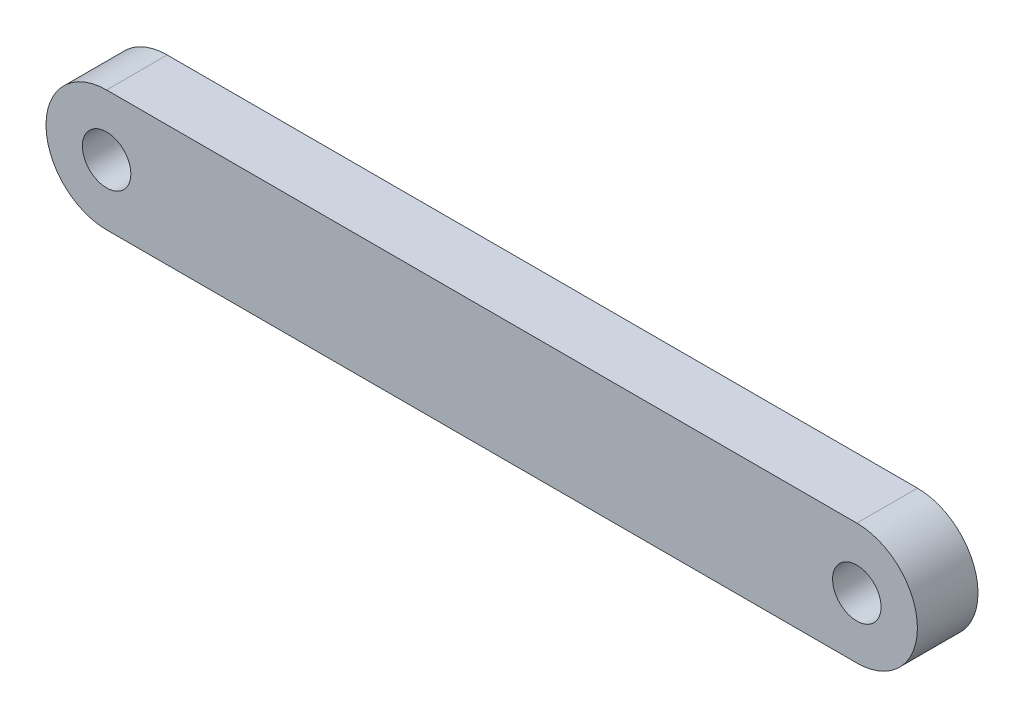
SolidWorks part; units mm, degrees
ref_plane "前基準面" through (0, 0, 0) normal (0, 0, 1) x (1, 0, 0)
ref_plane "上基準面" through (0, 0, 0) normal (0, 1, 0) x (1, 0, 0)
ref_plane "右基準面" through (0, 0, 0) normal (1, 0, 0) x (0, 0, -1)
sketch "草圖2" plane through (0, 0, 0) normal (0, 0, 1) x (1, 0, 0)
  line L0 (-30.95, 0) -> (30.95, 0) construction
  line L1 (-30.95, 5) -> (30.95, 5)
  line L2 (-30.95, -5) -> (30.95, -5)
  arc A0 (-30.95, 5) -> (-30.95, -5) centre (-30.95, 0) ccw
  arc A1 (30.95, -5) -> (30.95, 5) centre (30.95, 0) ccw
  circle A2 centre (30.95, 0) radius 2
  circle A3 centre (-30.95, 0) radius 2
  point P2 (0, 0)
  dimension "D2" = 4
  dimension "D3" = 5
  dimension "D1" = 61.9
extrude "填料-伸長1" add sketch "草圖2" along normal mid plane 5
